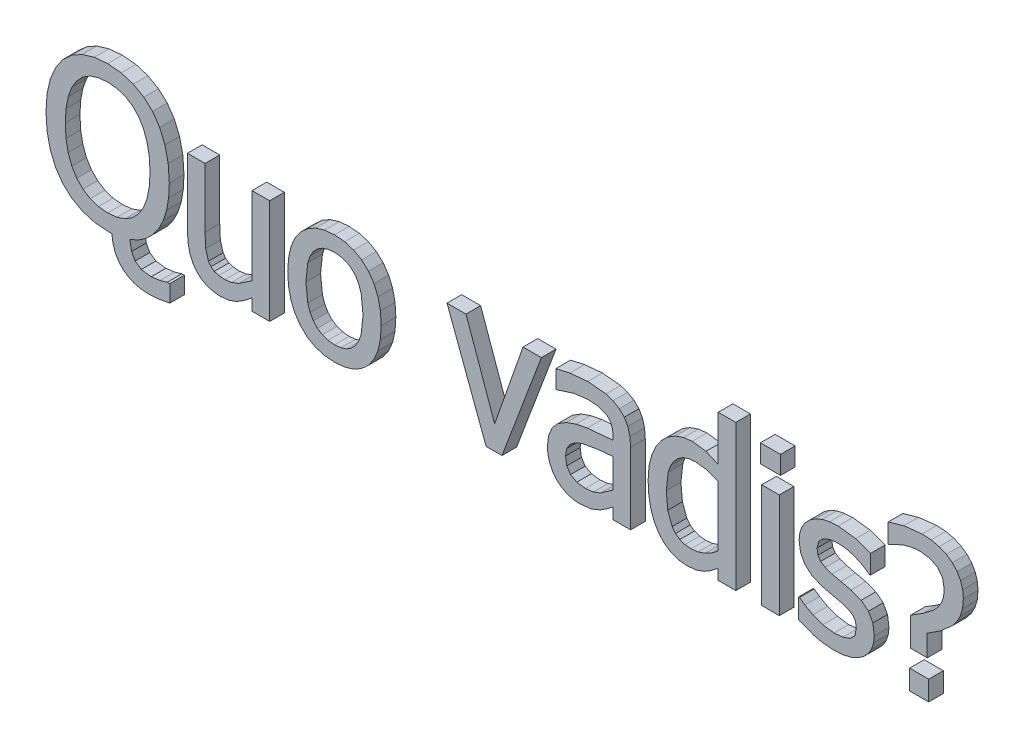
SolidWorks part; units mm, degrees
ref_plane "Front Plane" through (0, 0, 0) normal (0, 0, 1) x (1, 0, 0)
ref_plane "Top Plane" through (0, 0, 0) normal (0, 1, 0) x (1, 0, 0)
ref_plane "Right Plane" through (0, 0, 0) normal (1, 0, 0) x (0, 0, -1)
ref_plane "Plane2" through (0, 0, 21.9456) normal (0, 0, 1) x (1, 0, 0)
sketch "Sketch5" plane through (0, 0, 21.9456) normal (0, 0, 1) x (1, 0, 0)
  line L0 (3032.2526, 1582.4249) -> (3031.3416, 1603.0953)
  line L1 (3031.3416, 1603.0953) -> (3031.3416, 1692.2231)
  line L2 (3031.3416, 1692.2231) -> (3004.9953, 1692.2231)
  line L3 (3004.9953, 1692.2231) -> (3004.9953, 1590.623)
  line L4 (3004.9953, 1590.623) -> (3005.924, 1575.9785)
  line L5 (3005.924, 1575.9785) -> (3008.7092, 1563.7165)
  line L6 (3008.7092, 1563.7165) -> (3013.176, 1553.5916)
  line L7 (3013.176, 1553.5916) -> (3019.1495, 1545.3584)
  line L8 (3019.1495, 1545.3584) -> (3026.4542, 1539.0522)
  line L9 (3026.4542, 1539.0522) -> (3034.915, 1534.7079)
  line L10 (3034.915, 1534.7079) -> (3044.2517, 1532.1856)
  line L11 (3044.2517, 1532.1856) -> (3054.184, 1531.3448)
  line L12 (3054.184, 1531.3448) -> (3067.0066, 1532.7286)
  line L13 (3067.0066, 1532.7286) -> (3078.5682, 1536.8801)
  line L14 (3078.5682, 1536.8801) -> (3089.8142, 1543.6943)
  line L15 (3089.8142, 1543.6943) -> (3101.6908, 1553.0661)
  line L16 (3101.6908, 1553.0661) -> (3101.6908, 1535.6889)
  line L17 (3101.6908, 1535.6889) -> (3128.0367, 1535.6889)
  line L18 (3128.0367, 1535.6889) -> (3128.0367, 1692.2231)
  line L19 (3128.0367, 1692.2231) -> (3101.6908, 1692.2231)
  line L20 (3101.6908, 1692.2231) -> (3101.6908, 1575.348)
  line L21 (3101.6908, 1575.348) -> (3081.651, 1561.8947)
  line L22 (3081.651, 1561.8947) -> (3071.0354, 1557.7958)
  line L23 (3071.0354, 1557.7958) -> (3061.0507, 1556.4294)
  line L24 (3061.0507, 1556.4294) -> (3051.8894, 1557.1301)
  line L25 (3051.8894, 1557.1301) -> (3045.145, 1559.2322)
  line L26 (3045.145, 1559.2322) -> (3040.1876, 1562.8407)
  line L27 (3040.1876, 1562.8407) -> (3036.3865, 1568.0608)
  line L28 (3036.3865, 1568.0608) -> (3032.2526, 1582.4249)
extrude "Boss-Extrude2" add sketch "Sketch5" against normal blind 21.9456 separate body
sketch "Sketch10" plane through (0, 0, 21.9456) normal (0, 0, 1) x (1, 0, 0)
  line L0 (2865.3305, 1533.2891) -> (2885.4578, 1531.4848)
  line L1 (2885.4578, 1531.4848) -> (2891.9044, 1531.4848)
  line L2 (2891.9044, 1531.4848) -> (2893.4326, 1519.9934)
  line L3 (2893.4326, 1519.9934) -> (2896.6165, 1509.9036)
  line L4 (2896.6165, 1509.9036) -> (2901.4554, 1501.2151)
  line L5 (2901.4554, 1501.2151) -> (2907.9502, 1493.928)
  line L6 (2907.9502, 1493.928) -> (2915.8196, 1488.1647)
  line L7 (2915.8196, 1488.1647) -> (2924.7842, 1484.0481)
  line L8 (2924.7842, 1484.0481) -> (2934.8435, 1481.5782)
  line L9 (2934.8435, 1481.5782) -> (2945.9977, 1480.7549)
  line L10 (2945.9977, 1480.7549) -> (2962.6038, 1481.7358)
  line L11 (2962.6038, 1481.7358) -> (2978.5094, 1484.6787)
  line L12 (2978.5094, 1484.6787) -> (2978.5094, 1509.9036)
  line L13 (2978.5094, 1509.9036) -> (2974.7257, 1509.9036)
  line L14 (2974.7257, 1509.9036) -> (2963.7949, 1506.7505)
  line L15 (2963.7949, 1506.7505) -> (2950.6218, 1504.9988)
  line L16 (2950.6218, 1504.9988) -> (2935.8375, 1507.0308)
  line L17 (2935.8375, 1507.0308) -> (2926.6584, 1513.407)
  line L18 (2926.6584, 1513.407) -> (2921.4032, 1523.2867)
  line L19 (2921.4032, 1523.2867) -> (2918.6707, 1537.3706)
  line L20 (2918.6707, 1537.3706) -> (2931.6773, 1543.125)
  line L21 (2931.6773, 1543.125) -> (2943.2297, 1550.999)
  line L22 (2943.2297, 1550.999) -> (2953.3286, 1560.9926)
  line L23 (2953.3286, 1560.9926) -> (2961.9732, 1573.1058)
  line L24 (2961.9732, 1573.1058) -> (2968.9014, 1587.1634)
  line L25 (2968.9014, 1587.1634) -> (2973.8498, 1602.9903)
  line L26 (2973.8498, 1602.9903) -> (2976.819, 1620.5863)
  line L27 (2976.819, 1620.5863) -> (2977.809, 1639.9516)
  line L28 (2977.809, 1639.9516) -> (2976.1622, 1664.5808)
  line L29 (2976.1622, 1664.5808) -> (2971.2222, 1686.3372)
  line L30 (2971.2222, 1686.3372) -> (2963.3045, 1705.0107)
  line L31 (2963.3045, 1705.0107) -> (2952.724, 1720.3908)
  line L32 (2952.724, 1720.3908) -> (2939.6212, 1732.3375)
  line L33 (2939.6212, 1732.3375) -> (2923.8555, 1741.2714)
  line L34 (2923.8555, 1741.2714) -> (2905.7076, 1746.8418)
  line L35 (2905.7076, 1746.8418) -> (2885.4578, 1748.6986)
  line L36 (2885.4578, 1748.6986) -> (2865.4358, 1746.8944)
  line L37 (2865.4358, 1746.8944) -> (2847.4107, 1741.4814)
  line L38 (2847.4107, 1741.4814) -> (2831.6276, 1732.6002)
  line L39 (2831.6276, 1732.6002) -> (2818.332, 1720.3908)
  line L40 (2818.332, 1720.3908) -> (2807.6639, 1704.6952)
  line L41 (2807.6639, 1704.6952) -> (2799.7634, 1686.197)
  line L42 (2799.7634, 1686.197) -> (2794.8761, 1664.686)
  line L43 (2794.8761, 1664.686) -> (2793.247, 1639.9516)
  line L44 (2793.247, 1639.9516) -> (2794.8587, 1615.6377)
  line L45 (2794.8587, 1615.6377) -> (2799.6936, 1593.9864)
  line L46 (2799.6936, 1593.9864) -> (2807.5411, 1575.2778)
  line L47 (2807.5411, 1575.2778) -> (2818.1918, 1559.7926)
  line L48 (2818.1918, 1559.7926) -> (2831.4874, 1547.5831)
  line L49 (2831.4874, 1547.5831) -> (2847.2703, 1538.7019)
  line L50 (2847.2703, 1538.7019) -> (2865.3305, 1533.2891)
  line L51 (2885.5982, 1555.1682) -> (2871.8295, 1556.5344)
  line L52 (2871.8295, 1556.5344) -> (2859.5324, 1560.6335)
  line L53 (2859.5324, 1560.6335) -> (2848.7067, 1567.4652)
  line L54 (2848.7067, 1567.4652) -> (2839.3524, 1577.0297)
  line L55 (2839.3524, 1577.0297) -> (2831.8112, 1589.1603)
  line L56 (2831.8112, 1589.1603) -> (2826.4248, 1603.691)
  line L57 (2826.4248, 1603.691) -> (2823.1928, 1620.6213)
  line L58 (2823.1928, 1620.6213) -> (2822.1154, 1639.9516)
  line L59 (2822.1154, 1639.9516) -> (2823.2191, 1659.2206)
  line L60 (2823.2191, 1659.2206) -> (2826.5297, 1676.3874)
  line L61 (2826.5297, 1676.3874) -> (2831.9077, 1691.137)
  line L62 (2831.9077, 1691.137) -> (2839.2124, 1703.1538)
  line L63 (2839.2124, 1703.1538) -> (2848.5491, 1712.7707)
  line L64 (2848.5491, 1712.7707) -> (2859.1821, 1719.4798)
  line L65 (2859.1821, 1719.4798) -> (2871.4266, 1723.4212)
  line L66 (2871.4266, 1723.4212) -> (2885.5982, 1724.7349)
  line L67 (2885.5982, 1724.7349) -> (2899.4541, 1723.3863)
  line L68 (2899.4541, 1723.3863) -> (2911.8738, 1719.3397)
  line L69 (2911.8738, 1719.3397) -> (2922.7171, 1712.5955)
  line L70 (2922.7171, 1712.5955) -> (2931.8435, 1703.1538)
  line L71 (2931.8435, 1703.1538) -> (2939.0607, 1691.2771)
  line L72 (2939.0607, 1691.2771) -> (2944.4559, 1676.6678)
  line L73 (2944.4559, 1676.6678) -> (2947.8192, 1659.5008)
  line L74 (2947.8192, 1659.5008) -> (2948.9405, 1639.9516)
  line L75 (2948.9405, 1639.9516) -> (2947.8674, 1620.6213)
  line L76 (2947.8674, 1620.6213) -> (2944.6487, 1603.691)
  line L77 (2944.6487, 1603.691) -> (2939.2841, 1589.1603)
  line L78 (2939.2841, 1589.1603) -> (2931.7734, 1577.0297)
  line L79 (2931.7734, 1577.0297) -> (2922.4501, 1567.4652)
  line L80 (2922.4501, 1567.4652) -> (2911.6461, 1560.6335)
  line L81 (2911.6461, 1560.6335) -> (2899.3621, 1556.5344)
  line L82 (2899.3621, 1556.5344) -> (2885.5982, 1555.1682)
extrude "Boss-Extrude3" add sketch "Sketch10" against normal blind 21.9456 separate body
sketch "Sketch15" plane through (0, 0, 21.9456) normal (0, 0, 1) x (1, 0, 0)
  line L0 (3265.5647, 1543.4446) -> (3275.8822, 1552.8558)
  line L1 (3275.8822, 1552.8558) -> (3284.2202, 1564.737)
  line L2 (3284.2202, 1564.737) -> (3290.1764, 1578.869)
  line L3 (3290.1764, 1578.869) -> (3293.7498, 1595.2519)
  line L4 (3293.7498, 1595.2519) -> (3294.9407, 1613.886)
  line L5 (3294.9407, 1613.886) -> (3293.7498, 1632.4674)
  line L6 (3293.7498, 1632.4674) -> (3290.1764, 1648.8328)
  line L7 (3290.1764, 1648.8328) -> (3284.2202, 1662.9823)
  line L8 (3284.2202, 1662.9823) -> (3275.8822, 1674.9159)
  line L9 (3275.8822, 1674.9159) -> (3265.5647, 1684.3884)
  line L10 (3265.5647, 1684.3884) -> (3253.6705, 1691.1545)
  line L11 (3253.6705, 1691.1545) -> (3240.1996, 1695.214)
  line L12 (3240.1996, 1695.214) -> (3225.1523, 1696.5672)
  line L13 (3225.1523, 1696.5672) -> (3210.1531, 1695.2096)
  line L14 (3210.1531, 1695.2096) -> (3196.6867, 1691.137)
  line L15 (3196.6867, 1691.137) -> (3184.7532, 1684.3491)
  line L16 (3184.7532, 1684.3491) -> (3174.3522, 1674.8459)
  line L17 (3174.3522, 1674.8459) -> (3165.9219, 1662.8904)
  line L18 (3165.9219, 1662.8904) -> (3159.9004, 1648.7453)
  line L19 (3159.9004, 1648.7453) -> (3156.2874, 1632.4104)
  line L20 (3156.2874, 1632.4104) -> (3155.0834, 1613.886)
  line L21 (3155.0834, 1613.886) -> (3156.2524, 1595.8213)
  line L22 (3156.2524, 1595.8213) -> (3159.7605, 1579.7448)
  line L23 (3159.7605, 1579.7448) -> (3165.6067, 1565.6565)
  line L24 (3165.6067, 1565.6565) -> (3173.7919, 1553.5566)
  line L25 (3173.7919, 1553.5566) -> (3184.0174, 1543.8389)
  line L26 (3184.0174, 1543.8389) -> (3195.986, 1536.8975)
  line L27 (3195.986, 1536.8975) -> (3209.6975, 1532.733)
  line L28 (3209.6975, 1532.733) -> (3225.1523, 1531.3448)
  line L29 (3225.1523, 1531.3448) -> (3240.1996, 1532.6892)
  line L30 (3240.1996, 1532.6892) -> (3253.6705, 1536.7224)
  line L31 (3253.6705, 1536.7224) -> (3265.5647, 1543.4446)
  line L32 (3264.9865, 1640.3896) -> (3267.7543, 1613.886)
  line L33 (3267.7543, 1613.886) -> (3264.9689, 1587.6627)
  line L34 (3264.9689, 1587.6627) -> (3261.4875, 1577.3757)
  line L35 (3261.4875, 1577.3757) -> (3256.6133, 1568.9718)
  line L36 (3256.6133, 1568.9718) -> (3250.469, 1562.4422)
  line L37 (3250.469, 1562.4422) -> (3243.1774, 1557.7781)
  line L38 (3243.1774, 1557.7781) -> (3234.7383, 1554.9798)
  line L39 (3234.7383, 1554.9798) -> (3225.1523, 1554.0471)
  line L40 (3225.1523, 1554.0471) -> (3215.4434, 1554.9974)
  line L41 (3215.4434, 1554.9974) -> (3206.9168, 1557.8482)
  line L42 (3206.9168, 1557.8482) -> (3199.5728, 1562.5998)
  line L43 (3199.5728, 1562.5998) -> (3193.4109, 1569.252)
  line L44 (3193.4109, 1569.252) -> (3188.5366, 1577.7435)
  line L45 (3188.5366, 1577.7435) -> (3185.0553, 1588.0131)
  line L46 (3185.0553, 1588.0131) -> (3182.2698, 1613.886)
  line L47 (3182.2698, 1613.886) -> (3185.0553, 1640.3896)
  line L48 (3185.0553, 1640.3896) -> (3188.5366, 1650.7115)
  line L49 (3188.5366, 1650.7115) -> (3193.4109, 1659.0804)
  line L50 (3193.4109, 1659.0804) -> (3199.5728, 1665.5487)
  line L51 (3199.5728, 1665.5487) -> (3206.9168, 1670.1688)
  line L52 (3206.9168, 1670.1688) -> (3215.4434, 1672.941)
  line L53 (3215.4434, 1672.941) -> (3225.1523, 1673.8648)
  line L54 (3225.1523, 1673.8648) -> (3234.7956, 1672.941)
  line L55 (3234.7956, 1672.941) -> (3243.2652, 1670.1688)
  line L56 (3243.2652, 1670.1688) -> (3250.561, 1665.5487)
  line L57 (3250.561, 1665.5487) -> (3256.6833, 1659.0804)
  line L58 (3256.6833, 1659.0804) -> (3261.5268, 1650.7115)
  line L59 (3261.5268, 1650.7115) -> (3264.9865, 1640.3896)
extrude "Boss-Extrude4" add sketch "Sketch15" against normal blind 21.9456 separate body
sketch "Sketch20" plane through (0, 0, 21.9456) normal (0, 0, 1) x (1, 0, 0)
  line L0 (3393.4579, 1692.2231) -> (3452.0354, 1535.6889)
  line L1 (3452.0354, 1535.6889) -> (3475.719, 1535.6889)
  line L2 (3475.719, 1535.6889) -> (3534.7168, 1692.2231)
  line L3 (3534.7168, 1692.2231) -> (3507.2498, 1692.2231)
  line L4 (3507.2498, 1692.2231) -> (3464.7882, 1571.4241)
  line L5 (3464.7882, 1571.4241) -> (3421.9058, 1692.2231)
  line L6 (3421.9058, 1692.2231) -> (3393.4579, 1692.2231)
extrude "Boss-Extrude5" add sketch "Sketch20" against normal blind 21.9456 separate body
sketch "Sketch25" plane through (0, 0, 21.9456) normal (0, 0, 1) x (1, 0, 0)
  line L0 (3587.759, 1557.3053) -> (3578.44, 1562.4553)
  line L1 (3578.44, 1562.4553) -> (3572.7644, 1570.9686)
  line L2 (3572.7644, 1570.9686) -> (3570.8725, 1582.7752)
  line L3 (3570.8725, 1582.7752) -> (3572.5892, 1593.3733)
  line L4 (3572.5892, 1593.3733) -> (3577.7392, 1601.3435)
  line L5 (3577.7392, 1601.3435) -> (3585.5169, 1607.1417)
  line L6 (3585.5169, 1607.1417) -> (3595.1164, 1611.2233)
  line L7 (3595.1164, 1611.2233) -> (3618.3093, 1615.3574)
  line L8 (3618.3093, 1615.3574) -> (3642.0627, 1617.6697)
  line L9 (3642.0627, 1617.6697) -> (3642.0627, 1574.2269)
  line L10 (3642.0627, 1574.2269) -> (3623.1439, 1560.9839)
  line L11 (3623.1439, 1560.9839) -> (3612.4585, 1556.9375)
  line L12 (3612.4585, 1556.9375) -> (3600.5816, 1555.5885)
  line L13 (3600.5816, 1555.5885) -> (3587.759, 1557.3053)
  line L14 (3642.0627, 1535.6889) -> (3668.2684, 1535.6889)
  line L15 (3668.2684, 1535.6889) -> (3668.2684, 1642.7543)
  line L16 (3668.2684, 1642.7543) -> (3667.2175, 1656.3476)
  line L17 (3667.2175, 1656.3476) -> (3664.0644, 1667.6989)
  line L18 (3664.0644, 1667.6989) -> (3658.7741, 1676.983)
  line L19 (3658.7741, 1676.983) -> (3651.3116, 1684.3753)
  line L20 (3651.3116, 1684.3753) -> (3641.9222, 1689.9458)
  line L21 (3641.9222, 1689.9458) -> (3631.412, 1693.4843)
  line L22 (3631.412, 1693.4843) -> (3604.2254, 1696.0068)
  line L23 (3604.2254, 1696.0068) -> (3577.3187, 1693.4843)
  line L24 (3577.3187, 1693.4843) -> (3556.4382, 1688.8597)
  line L25 (3556.4382, 1688.8597) -> (3556.4382, 1662.0934)
  line L26 (3556.4382, 1662.0934) -> (3557.9798, 1662.0934)
  line L27 (3557.9798, 1662.0934) -> (3582.644, 1670.0112)
  line L28 (3582.644, 1670.0112) -> (3604.085, 1672.7438)
  line L29 (3604.085, 1672.7438) -> (3619.0798, 1671.6928)
  line L30 (3619.0798, 1671.6928) -> (3631.412, 1667.4187)
  line L31 (3631.412, 1667.4187) -> (3635.8967, 1663.6875)
  line L32 (3635.8967, 1663.6875) -> (3639.2601, 1658.6599)
  line L33 (3639.2601, 1658.6599) -> (3641.362, 1652.091)
  line L34 (3641.362, 1652.091) -> (3642.0627, 1643.7354)
  line L35 (3642.0627, 1643.7354) -> (3642.0627, 1638.6904)
  line L36 (3642.0627, 1638.6904) -> (3603.3845, 1635.257)
  line L37 (3603.3845, 1635.257) -> (3586.6382, 1632.0163)
  line L38 (3586.6382, 1632.0163) -> (3572.274, 1626.9188)
  line L39 (3572.274, 1626.9188) -> (3559.4163, 1619.0184)
  line L40 (3559.4163, 1619.0184) -> (3550.5524, 1608.7708)
  line L41 (3550.5524, 1608.7708) -> (3545.4025, 1596.1409)
  line L42 (3545.4025, 1596.1409) -> (3543.6859, 1581.0935)
  line L43 (3543.6859, 1581.0935) -> (3544.6317, 1570.8461)
  line L44 (3544.6317, 1570.8461) -> (3547.4694, 1561.124)
  line L45 (3547.4694, 1561.124) -> (3551.8839, 1552.4179)
  line L46 (3551.8839, 1552.4179) -> (3557.5595, 1545.2183)
  line L47 (3557.5595, 1545.2183) -> (3564.6713, 1539.3676)
  line L48 (3564.6713, 1539.3676) -> (3572.8345, 1534.9883)
  line L49 (3572.8345, 1534.9883) -> (3581.7683, 1532.2555)
  line L50 (3581.7683, 1532.2555) -> (3591.1927, 1531.3448)
  line L51 (3591.1927, 1531.3448) -> (3609.4806, 1533.3066)
  line L52 (3609.4806, 1533.3066) -> (3623.004, 1538.9122)
  line L53 (3623.004, 1538.9122) -> (3633.4443, 1545.7088)
  line L54 (3633.4443, 1545.7088) -> (3642.0627, 1552.3654)
  line L55 (3642.0627, 1552.3654) -> (3642.0627, 1535.6889)
extrude "Boss-Extrude6" add sketch "Sketch25" against normal blind 21.9456 separate body
sketch "Sketch30" plane through (0, 0, 21.9456) normal (0, 0, 1) x (1, 0, 0)
  line L0 (4015.2321, 1663.6349) -> (4025.9004, 1656.4879)
  line L1 (4025.9004, 1656.4879) -> (4027.3018, 1656.4879)
  line L2 (4027.3018, 1656.4879) -> (4027.3018, 1684.6557)
  line L3 (4027.3018, 1684.6557) -> (4005.1599, 1692.7835)
  line L4 (4005.1599, 1692.7835) -> (3978.9541, 1696.0068)
  line L5 (3978.9541, 1696.0068) -> (3966.3682, 1695.1747)
  line L6 (3966.3682, 1695.1747) -> (3955.0958, 1692.6786)
  line L7 (3955.0958, 1692.6786) -> (3945.137, 1688.518)
  line L8 (3945.137, 1688.518) -> (3936.4922, 1682.6936)
  line L9 (3936.4922, 1682.6936) -> (3929.503, 1675.5465)
  line L10 (3929.503, 1675.5465) -> (3924.5105, 1667.4187)
  line L11 (3924.5105, 1667.4187) -> (3921.5152, 1658.3096)
  line L12 (3921.5152, 1658.3096) -> (3920.5167, 1648.2197)
  line L13 (3920.5167, 1648.2197) -> (3922.5485, 1633.9432)
  line L14 (3922.5485, 1633.9432) -> (3928.6447, 1621.9438)
  line L15 (3928.6447, 1621.9438) -> (3939.2252, 1612.5021)
  line L16 (3939.2252, 1612.5021) -> (3954.7105, 1605.8981)
  line L17 (3954.7105, 1605.8981) -> (3969.7051, 1602.2545)
  line L18 (3969.7051, 1602.2545) -> (3982.8782, 1599.3115)
  line L19 (3982.8782, 1599.3115) -> (3993.9313, 1595.703)
  line L20 (3993.9313, 1595.703) -> (4001.0262, 1591.3237)
  line L21 (4001.0262, 1591.3237) -> (4004.8618, 1585.4028)
  line L22 (4004.8618, 1585.4028) -> (4006.1412, 1577.1698)
  line L23 (4006.1412, 1577.1698) -> (4003.9687, 1566.239)
  line L24 (4003.9687, 1566.239) -> (3996.8917, 1559.3723)
  line L25 (3996.8917, 1559.3723) -> (3986.2413, 1555.6586)
  line L26 (3986.2413, 1555.6586) -> (3972.7881, 1554.1872)
  line L27 (3972.7881, 1554.1872) -> (3956.0416, 1556.5696)
  line L28 (3956.0416, 1556.5696) -> (3941.257, 1562.035)
  line L29 (3941.257, 1562.035) -> (3929.1351, 1568.7615)
  line L30 (3929.1351, 1568.7615) -> (3921.2174, 1574.6474)
  line L31 (3921.2174, 1574.6474) -> (3919.816, 1574.6474)
  line L32 (3919.816, 1574.6474) -> (3919.816, 1545.0783)
  line L33 (3919.816, 1545.0783) -> (3942.4481, 1536.1093)
  line L34 (3942.4481, 1536.1093) -> (3956.6195, 1532.9562)
  line L35 (3956.6195, 1532.9562) -> (3971.8072, 1531.9052)
  line L36 (3971.8072, 1531.9052) -> (3986.434, 1532.8162)
  line L37 (3986.434, 1532.8162) -> (3998.3633, 1535.5488)
  line L38 (3998.3633, 1535.5488) -> (4008.4004, 1540.0332)
  line L39 (4008.4004, 1540.0332) -> (4017.3521, 1546.1993)
  line L40 (4017.3521, 1546.1993) -> (4024.1313, 1553.2937)
  line L41 (4024.1313, 1553.2937) -> (4029.0532, 1561.6846)
  line L42 (4029.0532, 1561.6846) -> (4032.0492, 1570.9862)
  line L43 (4032.0492, 1570.9862) -> (4033.0477, 1580.8134)
  line L44 (4033.0477, 1580.8134) -> (4030.858, 1596.3687)
  line L45 (4030.858, 1596.3687) -> (4024.2891, 1608.2803)
  line L46 (4024.2891, 1608.2803) -> (4013.3758, 1616.9339)
  line L47 (4013.3758, 1616.9339) -> (3998.153, 1622.7146)
  line L48 (3998.153, 1622.7146) -> (3982.9481, 1626.1481)
  line L49 (3982.9481, 1626.1481) -> (3969.8453, 1629.1609)
  line L50 (3969.8453, 1629.1609) -> (3959.6851, 1632.6818)
  line L51 (3959.6851, 1632.6818) -> (3952.7483, 1637.0788)
  line L52 (3952.7483, 1637.0788) -> (3948.7545, 1643.1572)
  line L53 (3948.7545, 1643.1572) -> (3947.423, 1651.7231)
  line L54 (3947.423, 1651.7231) -> (3949.6653, 1661.3927)
  line L55 (3949.6653, 1661.3927) -> (3956.3918, 1668.2594)
  line L56 (3956.3918, 1668.2594) -> (3966.3765, 1672.3585)
  line L57 (3966.3765, 1672.3585) -> (3978.3936, 1673.7248)
  line L58 (3978.3936, 1673.7248) -> (3990.9534, 1672.5687)
  line L59 (3990.9534, 1672.5687) -> (4003.4084, 1669.1003)
  line L60 (4003.4084, 1669.1003) -> (4015.2321, 1663.6349)
extrude "Boss-Extrude7" add sketch "Sketch30" against normal blind 21.9456 separate body
sketch "Sketch35" plane through (0, 0, 21.9456) normal (0, 0, 1) x (1, 0, 0)
  line L0 (4053.7877, 1710.1607) -> (4055.3293, 1710.1607)
  line L1 (4055.3293, 1710.1607) -> (4075.439, 1719.9003)
  line L2 (4075.439, 1719.9003) -> (4088.2444, 1723.4212)
  line L3 (4088.2444, 1723.4212) -> (4101.8553, 1724.5948)
  line L4 (4101.8553, 1724.5948) -> (4116.3244, 1722.6504)
  line L5 (4116.3244, 1722.6504) -> (4127.7809, 1716.8171)
  line L6 (4127.7809, 1716.8171) -> (4135.2429, 1707.0252)
  line L7 (4135.2429, 1707.0252) -> (4137.7306, 1693.204)
  line L8 (4137.7306, 1693.204) -> (4136.6792, 1682.9915)
  line L9 (4136.6792, 1682.9915) -> (4133.5263, 1673.9351)
  line L10 (4133.5263, 1673.9351) -> (4128.4814, 1665.7895)
  line L11 (4128.4814, 1665.7895) -> (4121.7546, 1658.3096)
  line L12 (4121.7546, 1658.3096) -> (4105.4287, 1645.9074)
  line L13 (4105.4287, 1645.9074) -> (4087.141, 1634.4862)
  line L14 (4087.141, 1634.4862) -> (4087.141, 1591.7441)
  line L15 (4087.141, 1591.7441) -> (4112.2255, 1591.7441)
  line L16 (4112.2255, 1591.7441) -> (4112.2255, 1623.6955)
  line L17 (4112.2255, 1623.6955) -> (4132.4754, 1637.0087)
  line L18 (4132.4754, 1637.0087) -> (4149.642, 1652.0035)
  line L19 (4149.642, 1652.0035) -> (4156.4565, 1660.7796)
  line L20 (4156.4565, 1660.7796) -> (4161.7641, 1670.8521)
  line L21 (4161.7641, 1670.8521) -> (4165.1802, 1682.3257)
  line L22 (4165.1802, 1682.3257) -> (4166.3189, 1695.3061)
  line L23 (4166.3189, 1695.3061) -> (4165.2851, 1706.7055)
  line L24 (4165.2851, 1706.7055) -> (4162.1842, 1716.9398)
  line L25 (4162.1842, 1716.9398) -> (4157.0168, 1726.0094)
  line L26 (4157.0168, 1726.0094) -> (4149.7822, 1733.914)
  line L27 (4149.7822, 1733.914) -> (4140.7523, 1740.321)
  line L28 (4140.7523, 1740.321) -> (4130.198, 1744.8974)
  line L29 (4130.198, 1744.8974) -> (4118.1197, 1747.6431)
  line L30 (4118.1197, 1747.6431) -> (4104.5179, 1748.5585)
  line L31 (4104.5179, 1748.5585) -> (4077.4708, 1745.5455)
  line L32 (4077.4708, 1745.5455) -> (4053.7877, 1738.7488)
  line L33 (4053.7877, 1738.7488) -> (4053.7877, 1710.1607)
extrude "Boss-Extrude8" add sketch "Sketch35" against normal blind 21.9456 separate body
sketch "Sketch40" plane through (0, 0, 21.9456) normal (0, 0, 1) x (1, 0, 0)
  line L0 (3789.8731, 1566.642) -> (3779.6781, 1561.124)
  line L1 (3779.6781, 1561.124) -> (3769.2025, 1557.603)
  line L2 (3769.2025, 1557.603) -> (3758.7976, 1556.4294)
  line L3 (3758.7976, 1556.4294) -> (3749.7234, 1557.3447)
  line L4 (3749.7234, 1557.3447) -> (3741.9808, 1560.0905)
  line L5 (3741.9808, 1560.0905) -> (3735.5697, 1564.6669)
  line L6 (3735.5697, 1564.6669) -> (3730.4895, 1571.0738)
  line L7 (3730.4895, 1571.0738) -> (3723.8681, 1588.9589)
  line L8 (3723.8681, 1588.9589) -> (3721.6611, 1613.3254)
  line L9 (3721.6611, 1613.3254) -> (3724.5338, 1638.6728)
  line L10 (3724.5338, 1638.6728) -> (3728.1246, 1648.8109)
  line L11 (3728.1246, 1648.8109) -> (3733.1522, 1657.2586)
  line L12 (3733.1522, 1657.2586) -> (3739.4497, 1663.9109)
  line L13 (3739.4497, 1663.9109) -> (3746.8505, 1668.6624)
  line L14 (3746.8505, 1668.6624) -> (3755.3551, 1671.5132)
  line L15 (3755.3551, 1671.5132) -> (3764.9636, 1672.4635)
  line L16 (3764.9636, 1672.4635) -> (3781.8503, 1670.6418)
  line L17 (3781.8503, 1670.6418) -> (3799.4375, 1664.0553)
  line L18 (3799.4375, 1664.0553) -> (3799.4375, 1573.8064)
  line L19 (3799.4375, 1573.8064) -> (3789.8731, 1566.642)
  line L20 (3766.6452, 1532.8162) -> (3778.2767, 1536.9502)
  line L21 (3778.2767, 1536.9502) -> (3788.7869, 1543.1163)
  line L22 (3788.7869, 1543.1163) -> (3799.4375, 1551.6647)
  line L23 (3799.4375, 1551.6647) -> (3799.4375, 1535.6889)
  line L24 (3799.4375, 1535.6889) -> (3825.7835, 1535.6889)
  line L25 (3825.7835, 1535.6889) -> (3825.7835, 1753.7436)
  line L26 (3825.7835, 1753.7436) -> (3799.4375, 1753.7436)
  line L27 (3799.4375, 1753.7436) -> (3799.4375, 1685.9168)
  line L28 (3799.4375, 1685.9168) -> (3781.0793, 1693.9747)
  line L29 (3781.0793, 1693.9747) -> (3760.6192, 1696.5672)
  line L30 (3760.6192, 1696.5672) -> (3747.6041, 1695.1134)
  line L31 (3747.6041, 1695.1134) -> (3735.1844, 1690.7517)
  line L32 (3735.1844, 1690.7517) -> (3723.9556, 1683.8323)
  line L33 (3723.9556, 1683.8323) -> (3714.5138, 1674.7059)
  line L34 (3714.5138, 1674.7059) -> (3706.1408, 1662.5313)
  line L35 (3706.1408, 1662.5313) -> (3699.7995, 1648.4299)
  line L36 (3699.7995, 1648.4299) -> (3695.8053, 1631.9813)
  line L37 (3695.8053, 1631.9813) -> (3694.4742, 1612.7648)
  line L38 (3694.4742, 1612.7648) -> (3695.5252, 1594.144)
  line L39 (3695.5252, 1594.144) -> (3698.6783, 1577.8004)
  line L40 (3698.6783, 1577.8004) -> (3703.7582, 1563.8041)
  line L41 (3703.7582, 1563.8041) -> (3710.5899, 1552.2252)
  line L42 (3710.5899, 1552.2252) -> (3718.9808, 1543.2215)
  line L43 (3718.9808, 1543.2215) -> (3729.0182, 1536.67)
  line L44 (3729.0182, 1536.67) -> (3740.3519, 1532.676)
  line L45 (3740.3519, 1532.676) -> (3752.6314, 1531.3448)
  line L46 (3752.6314, 1531.3448) -> (3766.6452, 1532.8162)
extrude "Boss-Extrude9" add sketch "Sketch40" against normal blind 21.9456 separate body
sketch "Sketch45" plane through (0, 0, 21.9456) normal (0, 0, 1) x (1, 0, 0)
  line L0 (3862.6397, 1718.4289) -> (3892.6291, 1718.4289)
  line L1 (3892.6291, 1718.4289) -> (3892.6291, 1745.7558)
  line L2 (3892.6291, 1745.7558) -> (3862.6397, 1745.7558)
  line L3 (3862.6397, 1745.7558) -> (3862.6397, 1718.4289)
extrude "Boss-Extrude10" add sketch "Sketch45" against normal blind 21.9456 separate body
sketch "Sketch50" plane through (0, 0, 21.9456) normal (0, 0, 1) x (1, 0, 0)
  line L0 (3864.4614, 1535.6889) -> (3890.8074, 1535.6889)
  line L1 (3890.8074, 1535.6889) -> (3890.8074, 1692.2231)
  line L2 (3890.8074, 1692.2231) -> (3864.4614, 1692.2231)
  line L3 (3864.4614, 1692.2231) -> (3864.4614, 1535.6889)
extrude "Boss-Extrude11" add sketch "Sketch50" against normal blind 21.9456 separate body
sketch "Sketch55" plane through (0, 0, 21.9456) normal (0, 0, 1) x (1, 0, 0)
  line L0 (4085.8793, 1535.6889) -> (4114.4676, 1535.6889)
  line L1 (4114.4676, 1535.6889) -> (4114.4676, 1565.258)
  line L2 (4114.4676, 1565.258) -> (4085.8793, 1565.258)
  line L3 (4085.8793, 1565.258) -> (4085.8793, 1535.6889)
extrude "Boss-Extrude12" add sketch "Sketch55" against normal blind 21.9456 separate body
